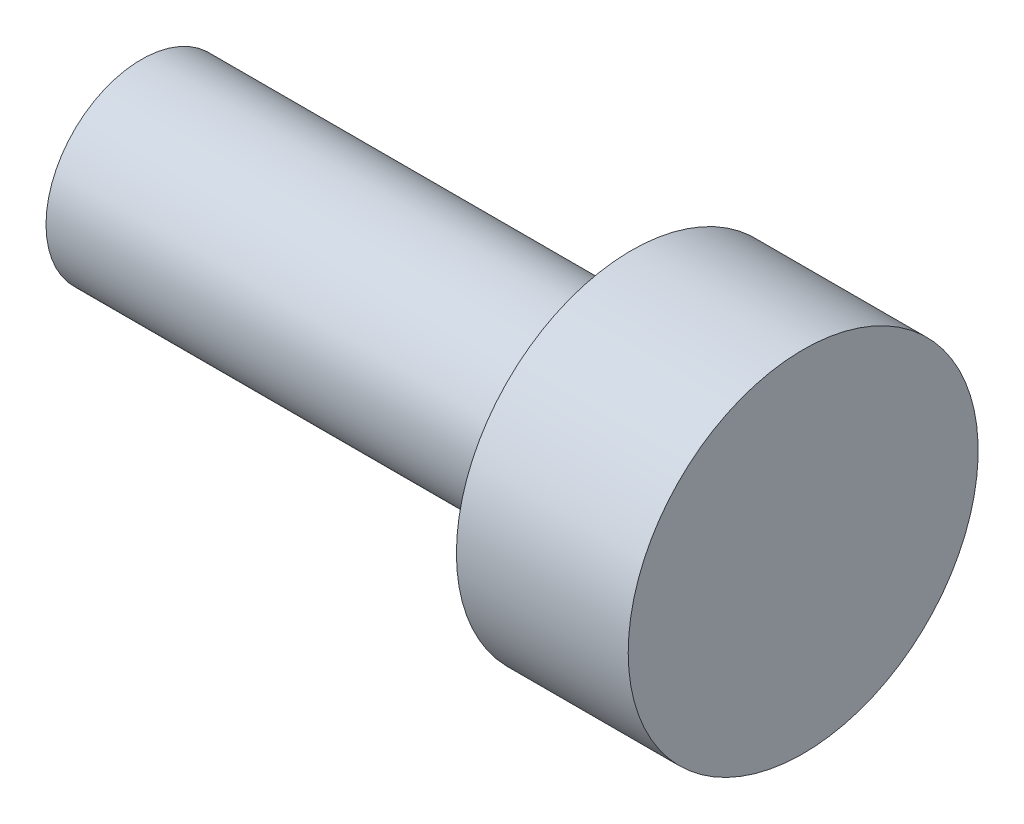
SolidWorks part; units mm, degrees
ref_plane "Front Plane" through (0, 0, 0) normal (0, 0, 1) x (1, 0, 0)
ref_plane "Top Plane" through (0, 0, 0) normal (0, 1, 0) x (1, 0, 0)
ref_plane "Right Plane" through (0, 0, 0) normal (1, 0, 0) x (0, 0, -1)
sketch "Axial profile (mm)" plane through (0, 0, 0) normal (0, 0, 1) x (1, 0, 0)
  line L0 (-110, 0) -> (75, 0) construction
  line L1 (132, 0) -> (142.4, 0)
  line L2 (142.4, 0) -> (142.4, 2.75)
  line L3 (142.4, 2.75) -> (139.7, 2.75)
  line L4 (139.7, 2.75) -> (139.7, 1.5)
  line L5 (139.7, 1.5) -> (132, 1.5)
  line L6 (132, 1.5) -> (132, 0)
revolve "Full revolution" add sketch "Axial profile (mm)" angle 360 about L0
